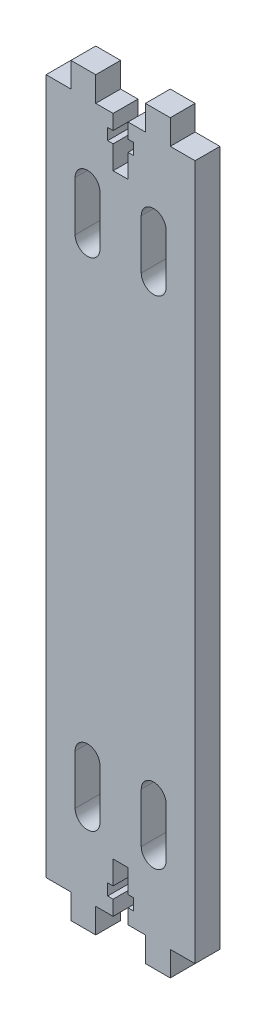
SolidWorks part; units mm, degrees
ref_plane "Front Plane" through (0, 0, 0) normal (0, 0, 1) x (1, 0, 0)
ref_plane "Top Plane" through (0, 0, 0) normal (0, 1, 0) x (1, 0, 0)
ref_plane "Right Plane" through (0, 0, 0) normal (1, 0, 0) x (0, 0, -1)
sketch "Sketch1" plane through (0, 0, 0) normal (0, 0, 1) x (1, 0, 0)
  line L0 (0, 72.0719) -> (0, -22.2682) construction
  line L1 (-15, 70) -> (-15, -70)
  line L2 (15, 70) -> (15, -70)
  line L3 (0, 0) -> (45.6439, 0) construction
  line L4 (-15, 70) -> (15, 70)
  line L5 (-15, -70) -> (15, -70)
  line L6 (-6.6565, -55) -> (-6.6565, -45) construction
  line L7 (-9.1565, -55) -> (-9.1565, -45)
  line L8 (-4.1565, -55) -> (-4.1565, -45)
  line L9 (6.6565, -55) -> (6.6565, -45) construction
  line L10 (9.1565, -55) -> (9.1565, -45)
  line L11 (4.1565, -55) -> (4.1565, -45)
  line L12 (6.6565, 55) -> (6.6565, 45) construction
  line L13 (9.1565, 55) -> (9.1565, 45)
  line L14 (4.1565, 55) -> (4.1565, 45)
  line L15 (-6.6565, 55) -> (-6.6565, 45) construction
  line L16 (-9.1565, 55) -> (-9.1565, 45)
  line L17 (-4.1565, 55) -> (-4.1565, 45)
  arc A0 (-9.1565, -55) -> (-4.1565, -55) centre (-6.6565, -55) ccw
  arc A1 (-4.1565, -45) -> (-9.1565, -45) centre (-6.6565, -45) ccw
  arc A2 (9.1565, -55) -> (4.1565, -55) centre (6.6565, -55) cw
  arc A3 (4.1565, -45) -> (9.1565, -45) centre (6.6565, -45) cw
  arc A4 (9.1565, 55) -> (4.1565, 55) centre (6.6565, 55) ccw
  arc A5 (4.1565, 45) -> (9.1565, 45) centre (6.6565, 45) ccw
  arc A6 (-9.1565, 55) -> (-4.1565, 55) centre (-6.6565, 55) cw
  arc A7 (-4.1565, 45) -> (-9.1565, 45) centre (-6.6565, 45) cw
  point P11 (-6.6565, -50)
  point P22 (6.6565, -50)
  point P29 (6.6565, 50)
  point P36 (-6.6565, 50)
  line B0 (-2.6, -67) -> (-2.6, -64.7)
  line B1 (1.5, -64.7) -> (1.5, -60)
  line B2 (-1.5, -60) -> (-1.5, -64.7)
  line B3 (-2.6, -64.7) -> (-1.5, -64.7)
  line B4 (0, -70) -> (0, -58.7792) construction
  line B5 (-1.5, -70) -> (-5, -70)
  line B6 (-5, -75) -> (-10, -75)
  line B7 (-10, -75) -> (-10, -70)
  line B8 (-5, -75) -> (-5, -70)
  line B9 (1.5, -70) -> (5, -70)
  line B10 (5, -70) -> (5, -75)
  line B11 (5, -75) -> (10, -75)
  line B12 (10, -75) -> (10, -70)
  line B13 (1.5, -70) -> (1.5, -67)
  line B14 (0, -60) -> (0, -70) construction
  line B15 (-1.5, -67) -> (-1.5, -70)
  line B16 (2.6, -64.7) -> (2.6, -67)
  line B17 (-1.5, -70) -> (1.5, -70) construction
  line B18 (1.5, -64.7) -> (2.6, -64.7)
  line B19 (2.6, -67) -> (1.5, -67)
  line B20 (1.5, -60) -> (-1.5, -60)
  line B21 (-1.5, -67) -> (-2.6, -67)
  line B22 (2.6, 67) -> (2.6, 64.7)
  line B23 (-1.5, 64.7) -> (-1.5, 60)
  line B24 (1.5, 60) -> (1.5, 64.7)
  line B25 (2.6, 64.7) -> (1.5, 64.7)
  line B26 (0, 70) -> (0, 58.7792) construction
  line B27 (1.5, 70) -> (5, 70)
  line B28 (5, 75) -> (10, 75)
  line B29 (10, 75) -> (10, 70)
  line B30 (5, 75) -> (5, 70)
  line B31 (-1.5, 70) -> (-5, 70)
  line B32 (-5, 70) -> (-5, 75)
  line B33 (-5, 75) -> (-10, 75)
  line B34 (-10, 75) -> (-10, 70)
  line B35 (-1.5, 70) -> (-1.5, 67)
  line B36 (0, 60) -> (0, 70) construction
  line B37 (1.5, 67) -> (1.5, 70)
  line B38 (-2.6, 64.7) -> (-2.6, 67)
  line B39 (1.5, 70) -> (-1.5, 70) construction
  line B40 (-1.5, 64.7) -> (-2.6, 64.7)
  line B41 (-2.6, 67) -> (-1.5, 67)
  line B42 (-1.5, 60) -> (1.5, 60)
  line B43 (1.5, 67) -> (2.6, 67)
  dimension "D1" = 140
  dimension "D2" = 5
  dimension "D3" = 30
  dimension "D4" = 10
  dimension "D5" = 20
sketch_block_instance "Insert M3 plots ep 5mm-1"
sketch_block "Insert M3 plots ep 5mm" parameters "D1"=10, "D2"=5, "D3"=5
sketch_block_instance "Decoupe Insert M3-4"
sketch_block "Decoupe Insert M3" parameters "D1"=5.2, "D2"=3, "D3"=2.3, "D4"=3, "D5"=10
sketch_block_instance "Insert M3 plots ep 5mm-2"
extrude "Boss-Extrude1" add sketch "Sketch1" along normal blind 5 contours B28 B30 L4 B29 | B37 B43 B22 B25 B24 B42 B23 B40 B38 B41 B35 L4 L1 L5 B15 B21 B0 B3 B2 B20 B1 B18 B16 B19 B13 L2 | B33 B34 L4 B32 | B6 B8 L5 B7 | B11 B12 L5 B10
